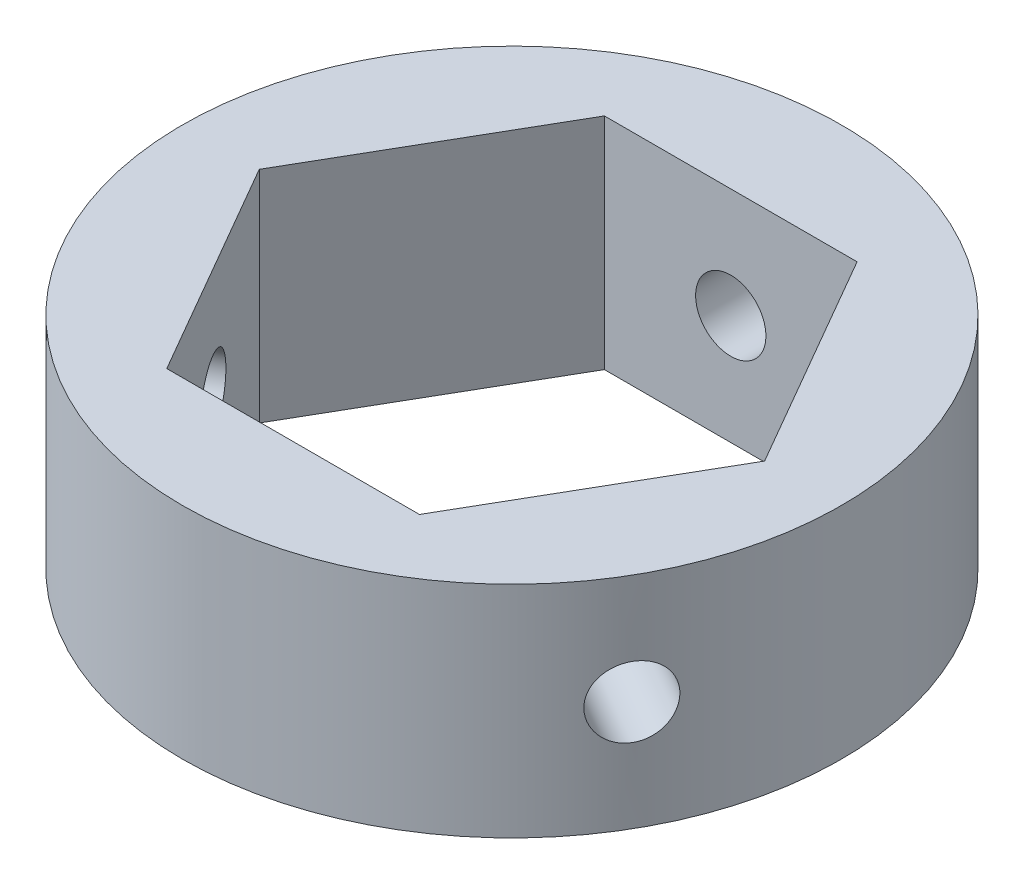
SolidWorks part; units mm, degrees
ref_plane "Front Plane" through (0, 0, 0) normal (0, 0, 1) x (1, 0, 0)
ref_plane "Top Plane" through (0, 0, 0) normal (0, 1, 0) x (1, 0, 0)
ref_plane "Right Plane" through (0, 0, 0) normal (1, 0, 0) x (0, 0, -1)
sketch "Sketch1" plane through (0, 0, 0) normal (0, 1, 0) x (1, 0, 0)
  circle A0 centre (0, 0) radius 15
  dimension "D1" = 30
extrude "Boss-Extrude1" add sketch "Sketch1" along normal blind 10
sketch "Sketch2" plane through (0, 10, 0) normal (0, 1, 0) x (1, 0, 0)
  line L1 (11.5, 0) -> (5.75, 9.9593)
  line L2 (5.75, 9.9593) -> (-5.75, 9.9593)
  line L3 (-5.75, 9.9593) -> (-11.5, 0)
  line L4 (-11.5, 0) -> (-5.75, -9.9593)
  line L5 (-5.75, -9.9593) -> (5.75, -9.9593)
  line L6 (5.75, -9.9593) -> (11.5, 0)
  circle A0 centre (0, 0) radius 9.9593 construction
  dimension "D1" = 11.5
extrude "Cut-Extrude1" cut sketch "Sketch2" against normal through all contours L3 L4 L5 L6 L1 L2
ref_plane "Plane2" through (-12.9904, 0, 7.5) normal (-0.866, 0, 0.5) x (0.5, 0, 0.866)
sketch "Sketch4" plane through (-12.9904, 0, 7.5) normal (-0.866, 0, 0.5) x (0.5, 0, 0.866)
  line L0 (15, 10) -> (-15, 10) construction
  circle A0 centre (0, 5) radius 1.6
  dimension "D1" = 3.2
  dimension "D2" = 5
extrude "Cut-Extrude2" cut sketch "Sketch4" against normal blind 10
pattern_circular "CirPattern2" count 3 every 120 about axis through (0, 10, 0) along (0, -1, 0) of "Cut-Extrude2"
